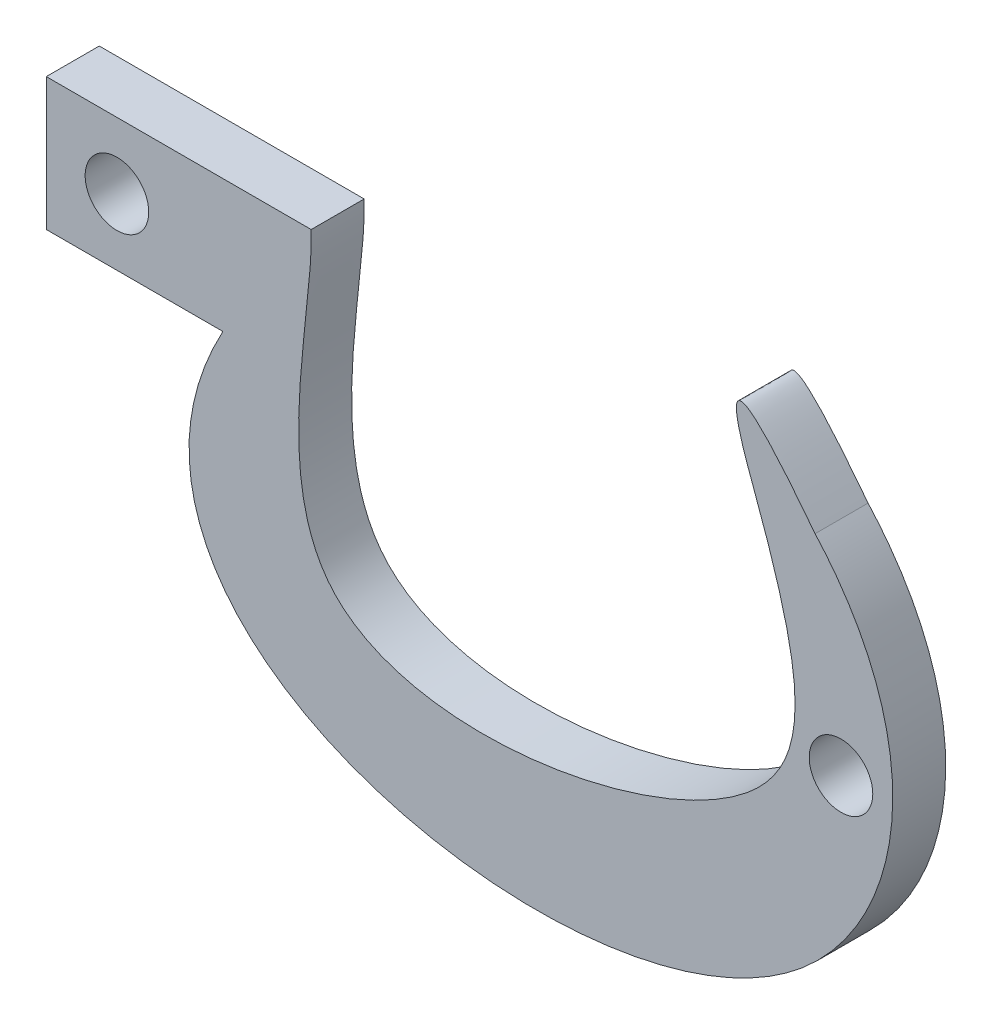
SolidWorks part; units mm, degrees
ref_plane "Plan de face" through (0, 0, 0) normal (0, 0, 1) x (1, 0, 0)
ref_plane "Plan de dessus" through (0, 0, 0) normal (0, 1, 0) x (1, 0, 0)
ref_plane "Plan de droite" through (0, 0, 0) normal (1, 0, 0) x (0, 0, -1)
sketch "Esquisse1" plane through (0, 0, 0) normal (0, 0, 1) x (1, 0, 0)
  line L1 (-9.1453, 11.1117) -> (0.8547, 11.1117)
  line L2 (-9.1453, 11.1117) -> (-9.1453, 3.6117)
  line L3 (-9.1453, 3.6117) -> (0.8547, 3.6117)
  line L5 (0.8547, 11.1117) -> (5.8547, 11.1117)
  circle A1 centre (-5.1453, 7.3617) radius 1.8
  circle A2 centre (35.8547, -0.669) radius 1.8
  spline S0 degree 3 poles (0.8547, 3.6117) (-8.9046, -14.3923) (36.8052, -24.6458) (41.105, 3.0168) (34.3894, 10.4632) knots 0 0 0 0 0.65763 1 1 1 1
  spline S1 degree 3 poles (5.8547, 11.1117) (6.0017, 6.8883) (0.3827, -13.0578) (35.1332, -6.838) (33.7788, 3.2404) (30.8547, 11.1117) knots 0 0 0 0 0.318182 0.727273 1 1 1 1
  spline S2 degree 2 poles (34.3894, 10.4632) (27.9016, 18.9315) (30.8547, 11.1117) knots 0 0 0 1 1 1
  point P4 (35.1667, 5.3624)
  point P7 (35.4591, 3.6117)
  point P8 (0, 0)
  point P9 (35.6662, 3.6117)
  point P12 (0, 0)
  point P13 (35.5056, 3.6117)
  point P22 (35.8547, 3.0506)
  point P23 (35.8547, -0.669)
  dimension "D7" = 4
  dimension "D1" = 10
  dimension "D2" = 7.5
  dimension "D8" = 3.75
extrude "Boss.-Extru.1" add sketch "Esquisse1" along normal blind 3
